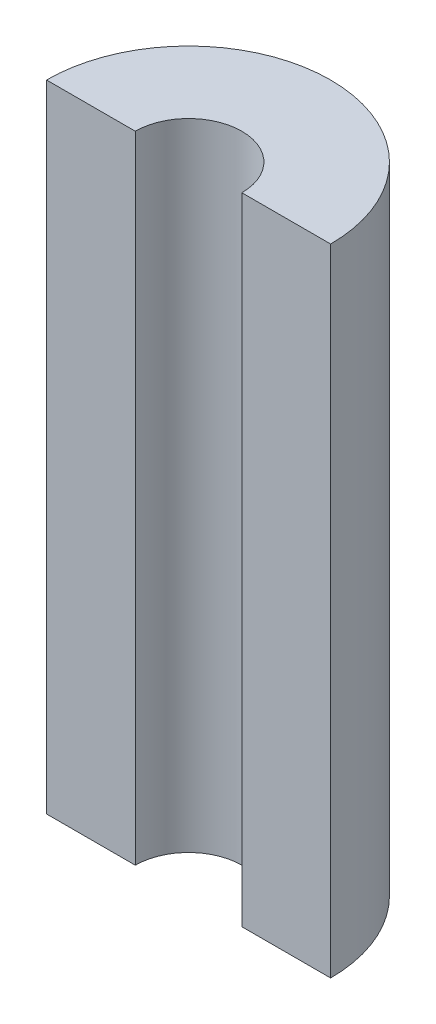
SolidWorks part; units mm, degrees
ref_plane "Front Plane" through (0, 0, 0) normal (0, 0, 1) x (1, 0, 0)
ref_plane "Top Plane" through (0, 0, 0) normal (0, 1, 0) x (1, 0, 0)
ref_plane "Right Plane" through (0, 0, 0) normal (1, 0, 0) x (0, 0, -1)
sketch "Sketch1" plane through (0, 0, 0) normal (0, 1, 0) x (1, 0, 0)
  circle A0 centre (0, 0) radius 80
  circle A1 centre (0, 0) radius 30
  dimension "D1" = 160
  dimension "D2" = 50
extrude "Boss-Extrude1" add sketch "Sketch1" along normal blind 358
split "Split1" trim tools "Front Plane" bodies to split 101 resulting bodies 103
